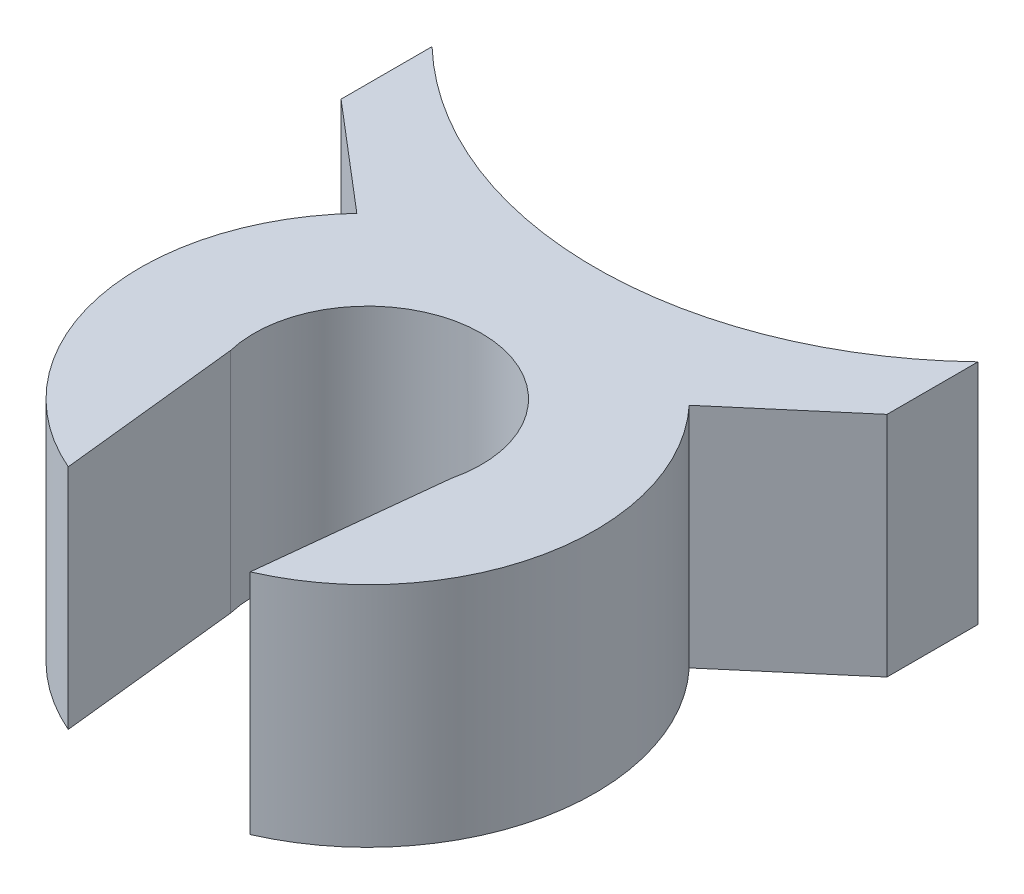
SolidWorks part; units mm, degrees
ref_plane "Front" through (0, 0, 0) normal (0, 0, 1) x (1, 0, 0)
ref_plane "Top" through (0, 0, 0) normal (0, 1, 0) x (1, 0, 0)
ref_plane "Right" through (0, 0, 0) normal (1, 0, 0) x (0, 0, -1)
sketch "Croquis1" plane through (0, 0, 0) normal (0, 1, 0) x (1, 0, 0)
  line L0 (0, 0) -> (0, 7) construction
  line L2 (-6, 7.4139) -> (-6, 3.4139)
  line L3 (-6, 3.4139) -> (-3.6531, 3.4139)
  line L4 (6, 7.4139) -> (6, 3.4139)
  line L5 (3.6531, 3.4139) -> (6, 3.4139)
  circle A0 centre (0, 0) radius 2.5
  arc A1 (-3.6531, 3.4139) -> (3.6531, 3.4139) centre (0, 0) ccw
  arc A2 (-6, 7.4139) -> (6, 7.4139) centre (0, 13.6636) ccw
  dimension "D1" = 5
  dimension "D2" = 10
  dimension "D3" = 7
  dimension "D4" = 4
  dimension "D5" = 6
  dimension "D6" = 12
extrude "Saliente-Extruir1" add sketch "Croquis1" along normal blind 5
sketch "Croquis2" plane through (0, 5, 0) normal (0, 1, 0) x (1, 0, 0)
  line L0 (0, 0) -> (0, -5) construction
  line L1 (-2, -4.5826) -> (-2.4312, -0.5826)
  line L2 (2, -4.5826) -> (2.4312, -0.5826)
  arc A0 (-3.6531, 3.4139) -> (3.6531, 3.4139) centre (0, 0) ccw construction
  circle A1 centre (0, 0) radius 2.5 construction
  arc A2 (-2.4312, -0.5826) -> (2.4312, -0.5826) centre (0, 0) ccw
  arc A3 (-2, -4.5826) -> (3.6531, 3.4139) centre (0, 0) ccw
  arc M7 (-3.6531, 3.4139) -> (3.6531, 3.4139) centre (0, 0) ccw
  circle M10 centre (0, 0) radius 2.5
  dimension "D1" = 2
  dimension "D2" = 4
extrude "Cortar-Extruir1" cut sketch "Croquis2" against normal blind 10 contours L0 A3 L2 M10 | L0 A2 L1 M7
sketch "Croquis3" plane through (0, 5, 0) normal (0, 1, 0) x (1, 0, 0)
  line L0 (3.6531, 3.4139) -> (6, 5.4139)
  line L1 (6, 3.4139) -> (6, 7.4139) construction
  line L2 (0, 2.5) -> (0, 5) construction
  line L3 (-3.6531, 3.4139) -> (-6, 5.4139)
  line L4 (3.6531, 3.4139) -> (6, 3.4139) construction
  line L5 (-6, 3.4139) -> (-3.6531, 3.4139) construction
  line L6 (-6, 7.4139) -> (-6, 3.4139) construction
  line L7 (6, 3.4139) -> (6, 5.4139)
  line L8 (3.6531, 3.4139) -> (6, 3.4139)
  line L9 (-6, 3.4139) -> (-3.6531, 3.4139)
  line L10 (-6, 5.4139) -> (-6, 3.4139)
  arc A0 (2.4312, -0.5826) -> (-2.4312, -0.5826) centre (0, 0) ccw construction
  arc A1 (-6, 7.4139) -> (6, 7.4139) centre (0, 13.6636) ccw construction
  point P2 (5, 4.7321)
  point P4 (0, 0)
  point P15 (6, 5.8267)
  dimension "D1" = 2
extrude "Cortar-Extruir2" cut sketch "Croquis3" against normal blind 10
